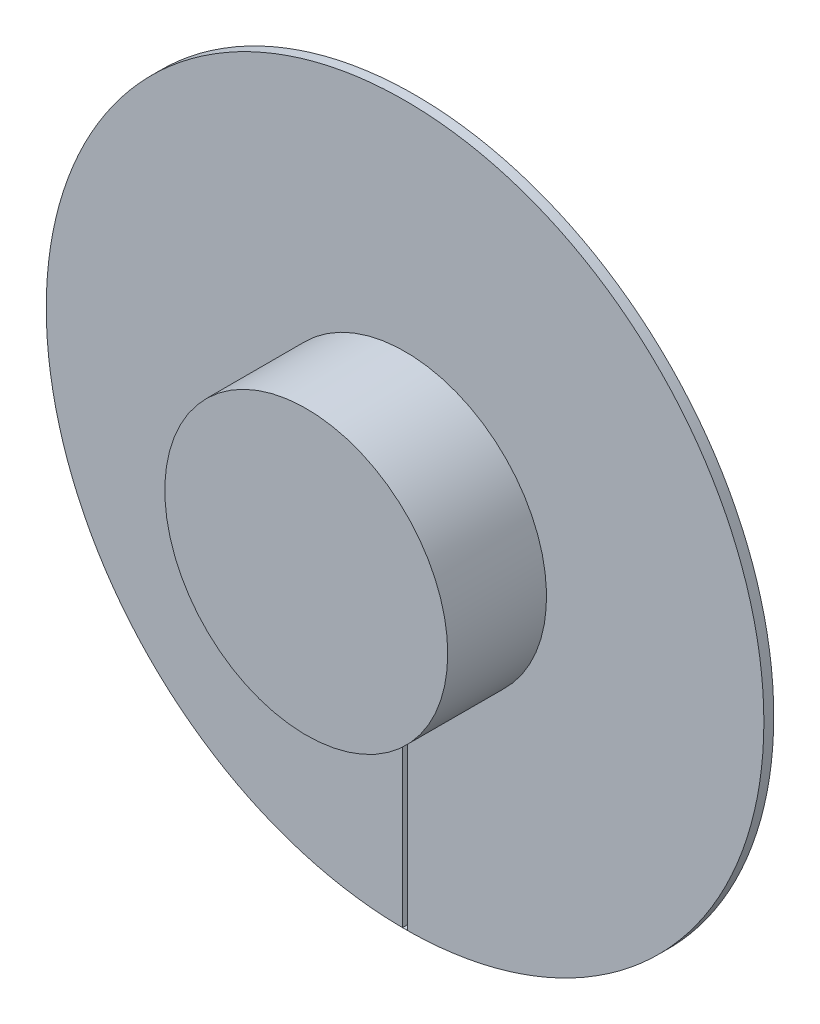
SolidWorks part; units mm, degrees
ref_plane "Plan de face" through (0, 0, 0) normal (0, 0, 1) x (1, 0, 0)
ref_plane "Plan de dessus" through (0, 0, 0) normal (0, 1, 0) x (1, 0, 0)
ref_plane "Plan de droite" through (0, 0, 0) normal (1, 0, 0) x (0, 0, -1)
sketch "Esquisse1" plane through (0, 0, 0) normal (0, 0, 1) x (1, 0, 0)
  circle A0 centre (0, 0) radius 363.2
  dimension "D1" = 726.4
extrude "Boss.-Extru.1" add sketch "Esquisse1" along normal blind 10
sketch "Esquisse2" plane through (0, 0, 10) normal (0, 0, 1) x (1, 0, 0)
  circle A0 centre (0, 0) radius 143.2
  dimension "D1" = 286.4
extrude "Boss.-Extru.2" add sketch "Esquisse2" along normal blind 100
sketch "Esquisse4" plane through (0, 0, 10) normal (0, 0, 1) x (1, 0, 0)
  line L0 (-2.5, -363.1) -> (-2.5, -143.1)
  line L1 (-2.5, -363.1) -> (2.5, -363.1)
  line L2 (-2.5, -143.1) -> (2.5, -143.1)
  line L3 (2.5, -363.1) -> (2.5, -143.1)
  line L4 (-2.5, -363.1) -> (2.5, -143.1) construction
  line L5 (-2.5, -143.1) -> (2.5, -363.1) construction
  circle A0 centre (0, 0) radius 143.2 construction
  point P1 (0, -253.1)
  dimension "D2" = 253.1
  dimension "D1" = 220
  dimension "D3" = 5
extrude "Enlèv. mat.-Extru.1" cut sketch "Esquisse4" against normal through all contours L0 L2 L3 L1
